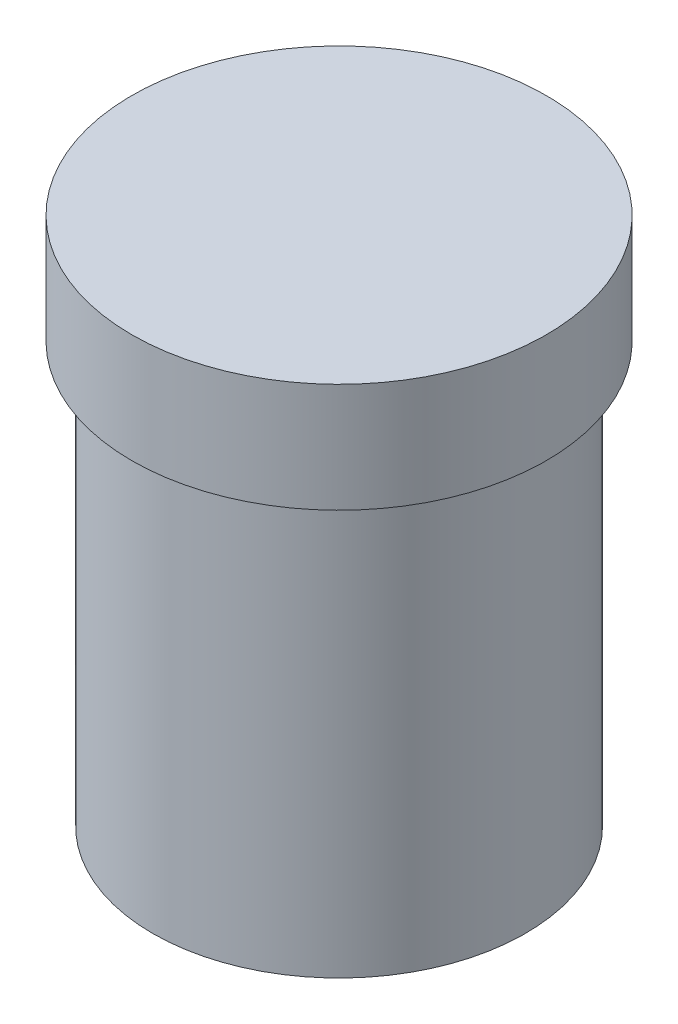
SolidWorks part; units mm, degrees
ref_plane "Front Plane" through (0, 0, 0) normal (0, 0, 1) x (1, 0, 0)
ref_plane "Top Plane" through (0, 0, 0) normal (0, 1, 0) x (1, 0, 0)
ref_plane "Right Plane" through (0, 0, 0) normal (1, 0, 0) x (0, 0, -1)
sketch "Sketch2" plane through (0, 0, 0) normal (0, 1, 0) x (1, 0, 0)
  circle A0 centre (0, 0) radius 10.25
  dimension "D1" = 20.5
extrude "Boss-Extrude1" add sketch "Sketch2" along normal blind 23.1
sketch "Sketch3" plane through (0, 23.1, 0) normal (0, 1, 0) x (1, 0, 0)
  circle A0 centre (0, 0) radius 11.4
  dimension "D1" = 22.8
extrude "Boss-Extrude2" add sketch "Sketch3" along normal blind 6
